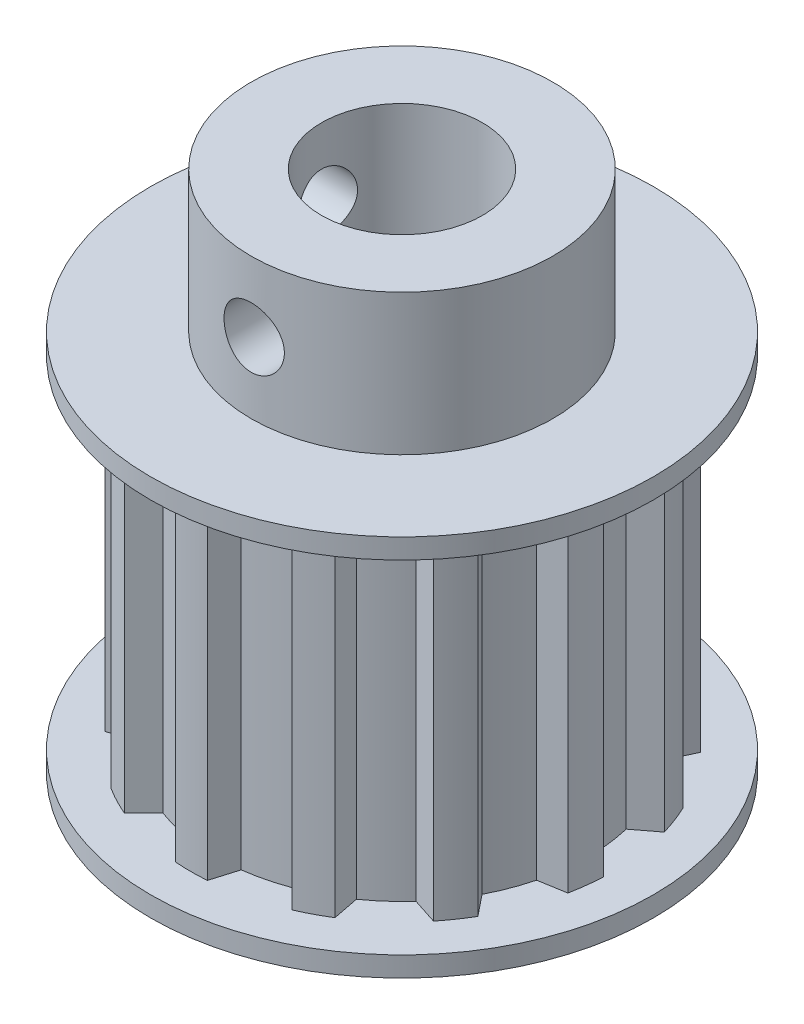
SolidWorks part; units mm, degrees
ref_plane "Alzado" through (0, 0, 0) normal (0, 0, 1) x (1, 0, 0)
ref_plane "Planta" through (0, 0, 0) normal (0, 1, 0) x (1, 0, 0)
ref_plane "Vista lateral" through (0, 0, 0) normal (1, 0, 0) x (0, 0, -1)
sketch "Croquis1" plane through (0, 0, 0) normal (0, 1, 0) x (1, 0, 0)
  circle A0 centre (0, 0) radius 12.5
  dimension "D1" = 25
extrude "Saliente-Extruir1" add sketch "Croquis1" along normal blind 1
sketch "Croquis3" plane through (0, 1, 0) normal (0, 1, 0) x (1, 0, 0)
  circle A0 centre (0, 0) radius 10.5
  dimension "D1" = 21
extrude "Saliente-Extruir2" add sketch "Croquis3" along normal blind 17
sketch "Croquis5" plane through (0, 18, 0) normal (0, 1, 0) x (1, 0, 0)
  line L0 (0, 10.55) -> (0, -10.55) construction
  line L1 (0, 9.25) -> (-1.05, 9.1902)
  line L2 (0, 9.25) -> (1.05, 9.1902)
  line L3 (1.05, 9.1902) -> (1.5451, 9.12) construction
  line L4 (-1.05, 9.1902) -> (-1.5451, 9.12) construction
  line L5 (-1.5451, 9.12) -> (-1.7622, 10.4018) construction
  line L6 (1.5451, 9.12) -> (1.7622, 10.4018) construction
  line L7 (-1.05, 9.1902) -> (-1.7622, 10.4018)
  line L8 (1.05, 9.1902) -> (1.7622, 10.4018)
  circle A0 centre (0, 0) radius 10.55
  circle A1 centre (0, 0) radius 9.25
  circle A3 centre (0, 0) radius 10.5
  circle A4 centre (0, 0) radius 10.5
  circle M2 centre (0, 0) radius 10.5
  dimension "D1" = 21.1
  dimension "D2" = 1.3
  dimension "D3" = 1.05
  dimension "D4" = 0.5
  dimension "D5" = 0.5
  dimension "D6" = 0
extrude "Cortar-Extruir1" cut sketch "Croquis5" against normal up to surface (17 mm away) contours A1 L8 L7 M2
pattern_circular "MatrizC1" count 13 over 360 about axis through (0, 0, 0) along (0, 1, 0) of "Cortar-Extruir1"
sketch "Croquis6" plane through (0, 18, 0) normal (0, 1, 0) x (1, 0, 0)
  circle A0 centre (0, 0) radius 12.5
  dimension "D1" = 25
extrude "Saliente-Extruir3" add sketch "Croquis6" along normal blind 1
sketch "Croquis7" plane through (0, 19, 0) normal (0, 1, 0) x (1, 0, 0)
  circle A0 centre (0, 0) radius 7.5
  dimension "D1" = 15
extrude "Saliente-Extruir4" add sketch "Croquis7" along normal blind 7
sketch "Croquis8" plane through (0, 26, 0) normal (0, 1, 0) x (1, 0, 0)
  circle A0 centre (0, 0) radius 7.5 construction
  circle A1 centre (0, 0) radius 7.5 construction
  point P0 (-7.5, 0)
  point P1 (0, -7.5)
ref_plane "Plano1" through (0, 26, 7.5) normal (0, 0, 1) x (1, 0, 0)
sketch "Croquis9" plane through (0, 26, 7.5) normal (0, 0, 1) x (1, 0, 0)
  line L0 (0, 0) -> (0, -7) construction
  line L1 (12.5, -7) -> (-12.5, -7) construction
  circle A0 centre (0, -3.5) radius 1.5
  dimension "D1" = 3
ref_plane "Plano2" through (-7.5, 26, 0) normal (-1, 0, 0) x (0, 0, 1)
sketch "Croquis10" plane through (-7.5, 26, 0) normal (-1, 0, 0) x (0, 0, 1)
  line L0 (0, 0) -> (0, -7) construction
  line L1 (12.5, -7) -> (-12.5, -7) construction
  circle A0 centre (0, -3.5) radius 1.5
  dimension "D1" = 3
sketch "Croquis11" plane through (0, 26, 0) normal (0, 1, 0) x (1, 0, 0)
  circle A0 centre (0, 0) radius 4
  dimension "D1" = 8
extrude "Cortar-Extruir2" cut sketch "Croquis11" against normal blind 37
extrude "Cortar-Extruir3" cut sketch "Croquis9" against normal blind 7
extrude "Cortar-Extruir4" cut sketch "Croquis10" against normal blind 7
